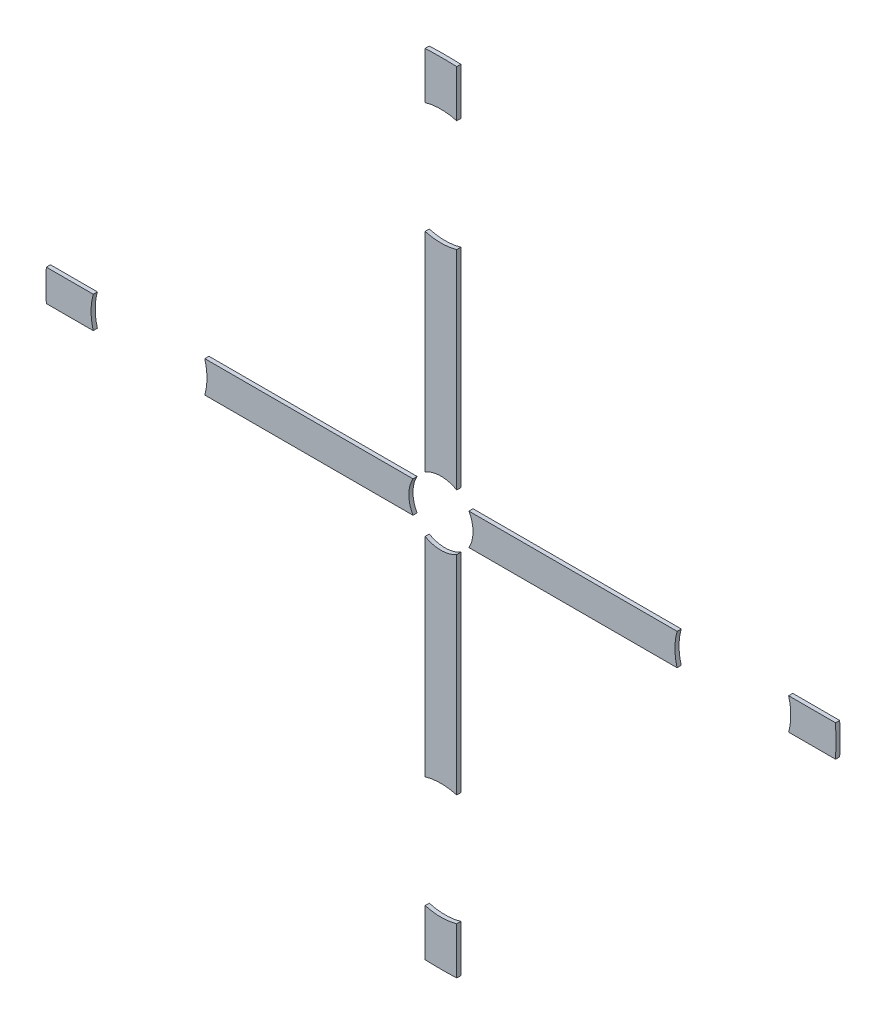
SolidWorks part; units mm, degrees
ref_plane "Front Plane" through (0, 0, 0) normal (0, 0, 1) x (1, 0, 0)
ref_plane "Top Plane" through (0, 0, 0) normal (0, 1, 0) x (1, 0, 0)
ref_plane "Right Plane" through (0, 0, 0) normal (1, 0, 0) x (0, 0, -1)
sketch "Sketch1" plane through (0, 0, 0) normal (0, 0, 1) x (1, 0, 0)
  point P0 (0, 0)
  line B0 (-583.7327, -23.3622) -> (-514.2802, -23.3622)
  line B1 (-514.2802, 23.3622) -> (-583.7327, 23.3622)
  line B2 (-23.3622, 583.7327) -> (-23.3622, 514.2802)
  line B3 (23.3622, 514.2802) -> (23.3622, 583.7327)
  line B4 (583.7327, 23.3622) -> (514.2802, 23.3622)
  line B5 (514.2802, -23.3622) -> (583.7327, -23.3622)
  line B6 (23.3622, -583.7327) -> (23.3622, -514.2802)
  line B7 (-23.3622, -514.2802) -> (-23.3622, -583.7327)
  line B8 (-23.3622, -41.3577) -> (-23.3622, -349.3198)
  line B9 (23.3622, -349.3198) -> (23.3622, -41.3577)
  line B10 (41.3577, -23.3622) -> (349.3198, -23.3622)
  line B11 (349.3198, 23.3622) -> (41.3577, 23.3622)
  line B12 (-23.3622, 349.3198) -> (-23.3622, 41.3577)
  line B13 (23.3622, 41.3577) -> (23.3622, 349.3198)
  line B14 (-41.3577, 23.3622) -> (-349.3198, 23.3622)
  line B15 (-349.3198, -23.3622) -> (-41.3577, -23.3622)
  arc B16 (-583.7327, 23.3622) -> (-583.7327, -23.3622) centre (0, 0) ccw
  arc B17 (-514.2802, 23.3622) -> (-514.2802, -23.3622) centre (-431.8, 0) ccw
  arc B18 (23.3622, 583.7327) -> (-23.3622, 583.7327) centre (0, 0) ccw
  arc B19 (23.3622, 514.2802) -> (-23.3622, 514.2802) centre (0, 431.8) ccw
  arc B20 (583.7327, -23.3622) -> (583.7327, 23.3622) centre (0, 0) ccw
  arc B21 (514.2802, -23.3622) -> (514.2802, 23.3622) centre (431.8, 0) ccw
  arc B22 (-23.3622, -583.7327) -> (23.3622, -583.7327) centre (0, 0) ccw
  arc B23 (-23.3622, -514.2802) -> (23.3622, -514.2802) centre (0, -431.8) ccw
  arc B24 (23.3622, -349.3198) -> (-23.3622, -349.3198) centre (0, -431.8) ccw
  arc B25 (-23.3622, -41.3577) -> (23.3622, -41.3577) centre (0, 0) ccw
  arc B26 (349.3198, 23.3622) -> (349.3198, -23.3622) centre (431.8, 0) ccw
  arc B27 (41.3577, -23.3622) -> (41.3577, 23.3622) centre (0, 0) ccw
  arc B28 (23.3622, 41.3577) -> (-23.3622, 41.3577) centre (0, 0) ccw
  arc B29 (-23.3622, 349.3198) -> (23.3622, 349.3198) centre (0, 431.8) ccw
  arc B30 (-349.3198, -23.3622) -> (-349.3198, 23.3622) centre (-431.8, 0) ccw
  arc B31 (-41.3577, 23.3622) -> (-41.3577, -23.3622) centre (0, 0) ccw
sketch_block_instance "Cross-1"
sketch_block "Cross"
extrude "Boss-Extrude1" add sketch "Sketch1" along normal blind 6.096
